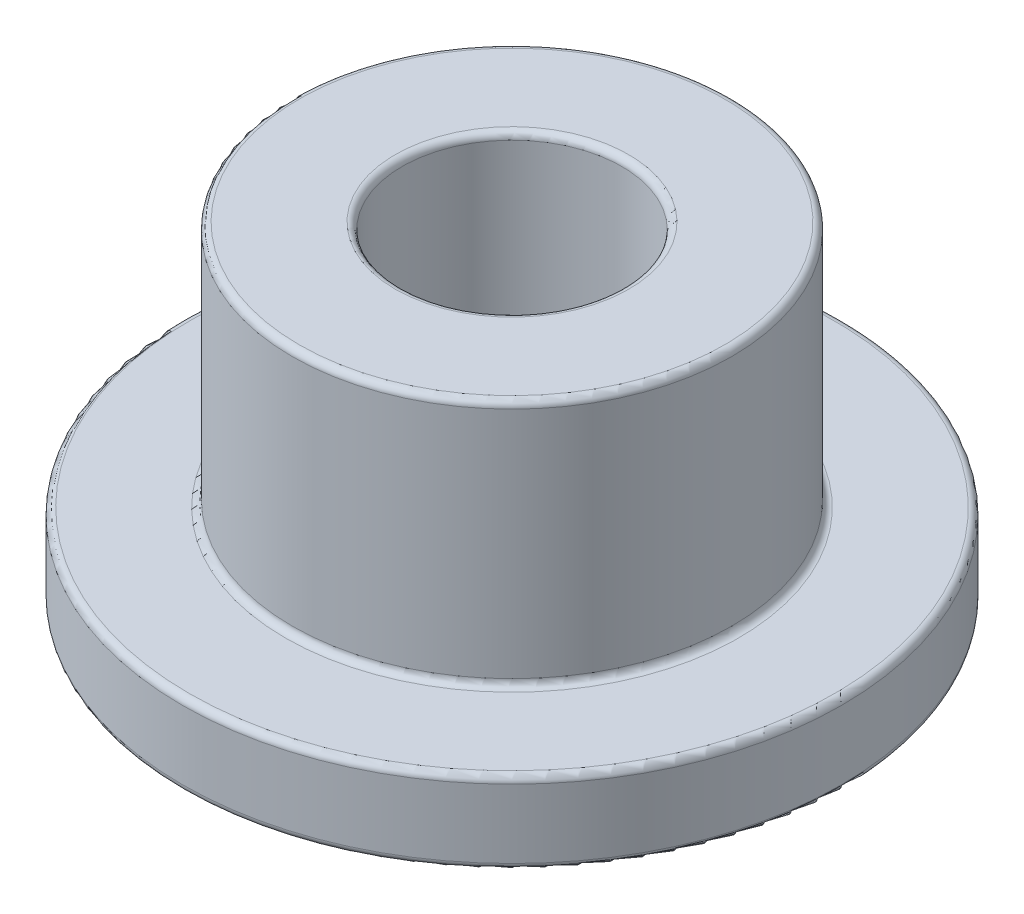
SolidWorks part; units mm, degrees
ref_plane "Front" through (0, 0, 0) normal (0, 0, 1) x (1, 0, 0)
ref_plane "Top" through (0, 0, 0) normal (0, 1, 0) x (1, 0, 0)
ref_plane "Right" through (0, 0, 0) normal (1, 0, 0) x (0, 0, -1)
sketch "Sketch1" plane through (0, 0, 0) normal (0, 1, 0) x (1, 0, 0)
  circle A0 centre (0, 0) radius 2
  circle A1 centre (0, 0) radius 4
  circle A2 centre (0, 0) radius 6
  dimension "ID" = 4
  dimension "OD" = 8
  dimension "FlangeOD" = 12
sketch "Sketch2" plane through (0, 0, 0) normal (1, 0, 0) x (0, 0, -1)
  line L0 (6, 0) -> (6, 1.5) construction
  line L1 (-4, 0) -> (-4, 6) construction
  line L8 (0, 0) -> (0, 6) construction
  point P5 (-6, 0)
  dimension "Flange Thickness" = 1.5
  dimension "Length" = 6
sketch "Sketch3" plane through (0, 0, 0) normal (0, 1, 0) x (1, 0, 0)
  circle A0 centre (0, 0) radius 2 construction
  circle A1 centre (0, 0) radius 4 construction
  circle A2 centre (0, 0) radius 2
  circle A3 centre (0, 0) radius 4
extrude "Boss-Extrude1" add sketch "Sketch3" along normal up to vertex (6 mm away) up to point (0, 6, 4)
sketch "Sketch4" plane through (0, 0, 0) normal (0, 1, 0) x (1, 0, 0)
  circle A0 centre (0, 0) radius 6 construction
  circle A1 centre (0, 0) radius 4 construction
  circle A2 centre (0, 0) radius 6
  circle A3 centre (0, 0) radius 4
extrude "Boss-Extrude2" add sketch "Sketch4" along normal up to vertex (1.5 mm away) up to point (0, 1.5, -6)
fillet "Fillet1" radius 0.125 6 edges at (0, 0, 2) (0, 0, 6) (0, 1.5, 4) (0, 1.5, 6) (0, 6, 2) (0, 6, 4)
